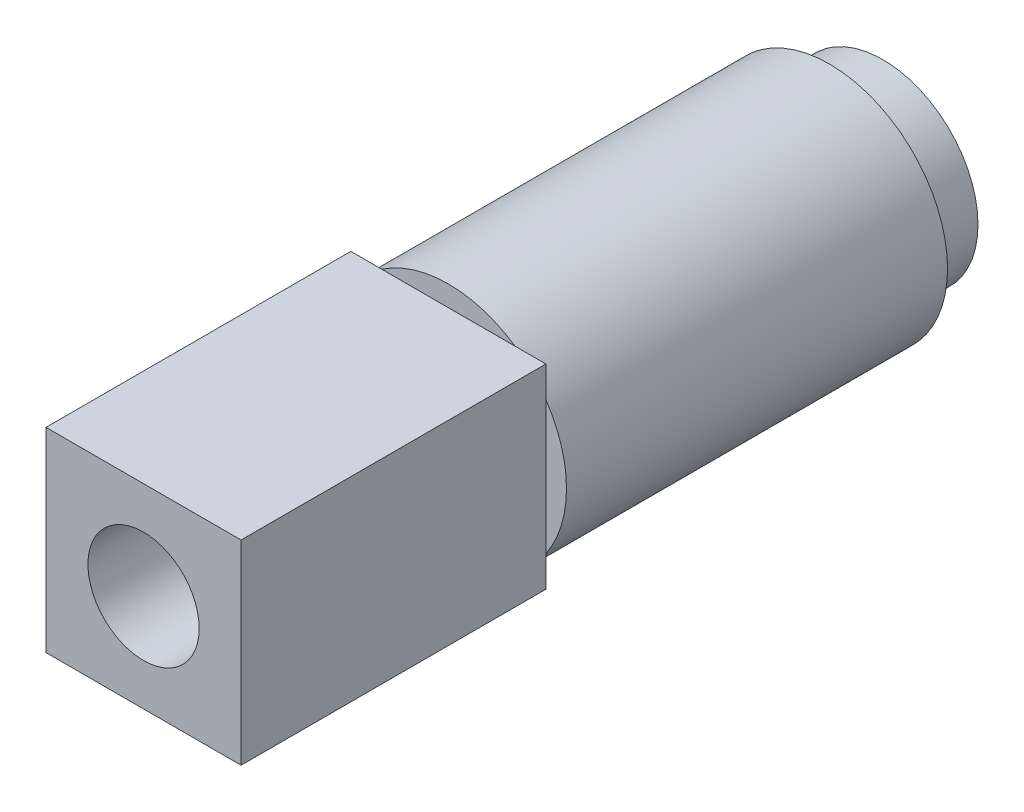
SolidWorks part; units mm, degrees
ref_plane "Front Plane" through (0, 0, 0) normal (0, 0, 1) x (1, 0, 0)
ref_plane "Top Plane" through (0, 0, 0) normal (0, 1, 0) x (1, 0, 0)
ref_plane "Right Plane" through (0, 0, 0) normal (1, 0, 0) x (0, 0, -1)
sketch "Sketch1" plane through (0, 0, 0) normal (0, 0, 1) x (1, 0, 0)
  circle A0 centre (0, 0) radius 1.5875
  dimension "D1" = 3.175
extrude "Boss-Extrude1" add sketch "Sketch1" along normal blind 0.889
sketch "Sketch2" plane through (0, 0, 0.889) normal (0, 0, 1) x (1, 0, 0)
  circle A0 centre (0, 0) radius 1.9685
  dimension "D1" = 3.937
extrude "Boss-Extrude2" add sketch "Sketch2" along normal blind 6.35
sketch "Sketch4" plane through (0, 0, 7.239) normal (0, 0, 1) x (1, 0, 0)
  line L1 (1.6256, -1.6256) -> (-1.6256, -1.6256)
  line L2 (1.6256, -1.6256) -> (1.6256, 1.6256)
  line L3 (1.6256, 1.6256) -> (-1.6256, 1.6256)
  line L4 (-1.6256, -1.6256) -> (-1.6256, 1.6256)
  line L5 (1.6256, -1.6256) -> (-1.6256, 1.6256) construction
  line L6 (1.6256, 1.6256) -> (-1.6256, -1.6256) construction
  point P0 (0, 0)
  point P5 (0, 0)
  dimension "D1" = 3.2512
  dimension "D2" = 3.2512
extrude "Boss-Extrude3" add sketch "Sketch4" along normal blind 5.08
sketch "Sketch5" plane through (0, 0, 12.319) normal (0, 0, 1) x (1, 0, 0)
  circle A0 centre (0, 0) radius 0.9271
  dimension "D1" = 1.8542
extrude "Cut-Extrude1" cut sketch "Sketch5" against normal blind 5.08
